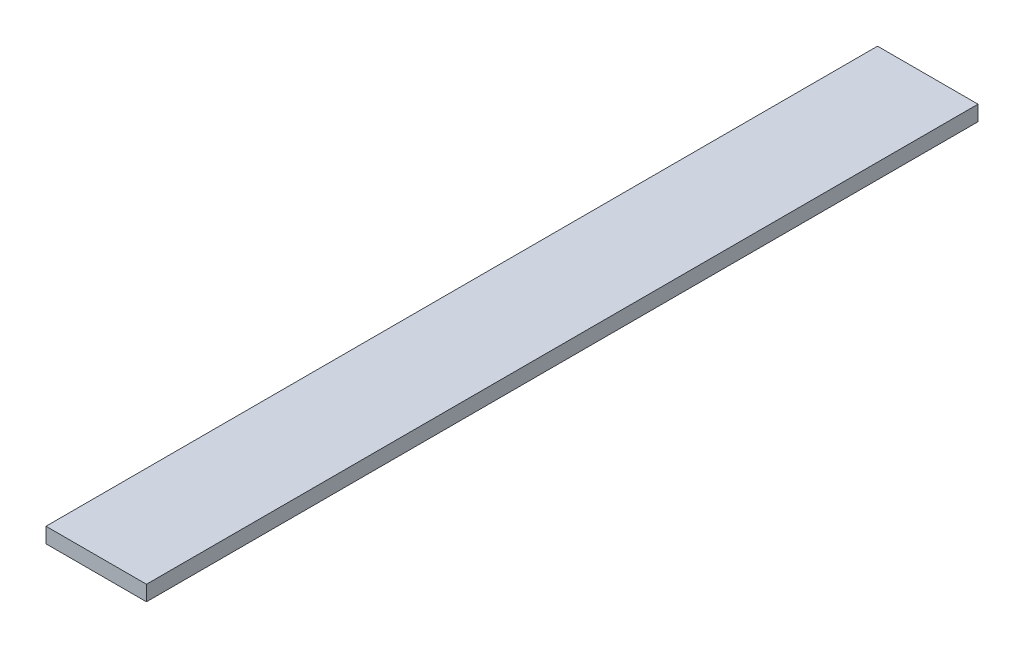
SolidWorks part; units mm, degrees
material "Pine"
ref_plane "Ön Düzlem" through (0, 0, 0) normal (0, 0, 1) x (1, 0, 0)
ref_plane "Üst Düzlem" through (0, 0, 0) normal (0, 1, 0) x (1, 0, 0)
ref_plane "Sağ Düzlem" through (0, 0, 0) normal (1, 0, 0) x (0, 0, -1)
sketch "Çizim1" plane through (0, 0, 0) normal (0, 1, 0) x (1, 0, 0)
  line L1 (-72.5, -600) -> (72.5, -600)
  line L2 (-72.5, -600) -> (-72.5, 600)
  line L3 (-72.5, 600) -> (72.5, 600)
  line L4 (72.5, -600) -> (72.5, 600)
  line L5 (-72.5, -600) -> (72.5, 600) construction
  line L6 (-72.5, 600) -> (72.5, -600) construction
  point P0 (0, 0)
  dimension "D1" = 145
  dimension "D2" = 1200
extrude "Yükseklik-Ekstrüzyon1" add sketch "Çizim1" along normal blind 22
